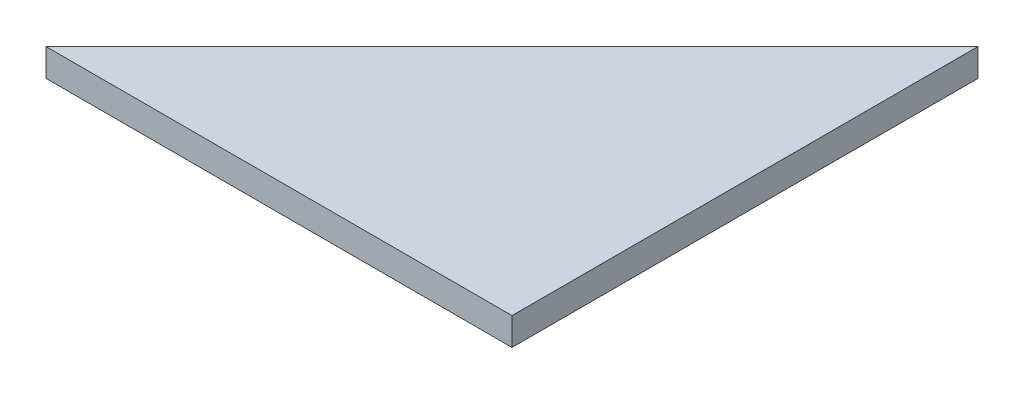
SolidWorks part; units mm, degrees
ref_plane "Front Plane" through (0, 0, 0) normal (0, 0, 1) x (1, 0, 0)
ref_plane "Top Plane" through (0, 0, 0) normal (0, 1, 0) x (1, 0, 0)
ref_plane "Right Plane" through (0, 0, 0) normal (1, 0, 0) x (0, 0, -1)
sketch "Sketch1" plane through (0, 0, 0) normal (0, 1, 0) x (1, 0, 0)
  line L0 (0, 0) -> (53.64, 53.64)
  line L1 (53.64, 53.64) -> (53.64, 0)
  line L2 (53.64, 0) -> (0, 0)
  line L3 (0, 0) -> (-14.0017, 0) construction
  dimension "D1" = 45
  dimension "D2" = 53.64
extrude "Boss-Extrude1" add sketch "Sketch1" along normal blind 3.175
sketch "Sketch2" plane through (0, 3.175, 0) normal (0, 1, 0) x (1, 0, 0)
  line L0 (33.64, -17.1503) -> (33.64, 13.412) construction
  line L1 (30.14, 3.175) -> (32.17, 3.175)
  line L2 (30.14, 3.175) -> (30.14, 0)
  line L3 (30.14, 0) -> (37.14, 0)
  line L4 (37.14, 3.175) -> (37.14, 0)
  line L5 (0, 0) -> (53.64, 0) construction
  line L6 (53.64, 0) -> (53.64, 53.64) construction
  line L7 (33.64, 9.925) -> (33.64, 3.175) construction
  line L8 (35.11, 7.85) -> (36.89, 7.85)
  line L9 (32.17, 9.925) -> (35.11, 9.925)
  line L10 (32.17, 9.925) -> (32.17, 7.85)
  line L12 (35.11, 9.925) -> (35.11, 7.85)
  line L13 (30.39, 7.85) -> (32.17, 7.85)
  line L14 (30.39, 7.85) -> (30.39, 5.25)
  line L15 (30.39, 5.25) -> (32.17, 5.25)
  line L16 (36.89, 7.85) -> (36.89, 5.25)
  line L17 (32.17, 5.25) -> (32.17, 3.175)
  line L18 (35.11, 5.25) -> (36.89, 5.25)
  line L19 (35.11, 5.25) -> (35.11, 3.175)
  line L20 (31.9575, 5.25) -> (35.7815, 5.25) construction
  line L21 (35.11, 3.175) -> (37.14, 3.175)
  line L22 (26.82, 26.82) -> (36.3598, 17.2802) construction
  line L23 (53.64, 53.64) -> (0, 0) construction
  line L24 (24.3451, 24.3451) -> (26.5902, 22.1001)
  line L25 (26.5902, 22.1001) -> (28.0256, 23.5355)
  line L26 (31.5399, 27.0498) -> (29.2949, 29.2949)
  line L27 (29.2949, 29.2949) -> (24.3451, 24.3451)
  line L28 (28.0256, 23.5355) -> (29.4964, 22.0647)
  line L29 (29.4964, 22.0647) -> (28.2377, 20.8061)
  line L30 (28.2377, 20.8061) -> (30.0762, 18.9676)
  line L31 (30.0762, 18.9676) -> (31.3349, 20.2262)
  line L32 (31.3349, 20.2262) -> (32.7986, 18.7625)
  line L33 (32.7986, 18.7625) -> (33.838, 19.802)
  line L34 (30.1045, 25.6144) -> (31.5753, 24.1436)
  line L35 (31.5753, 24.1436) -> (32.8339, 25.4023)
  line L36 (32.8339, 25.4023) -> (34.6724, 23.5638)
  line L37 (34.6724, 23.5638) -> (33.4138, 22.3051)
  line L38 (34.8775, 20.8414) -> (33.838, 19.802)
  line L39 (33.4138, 22.3051) -> (34.8775, 20.8414)
  line L40 (30.1045, 25.6144) -> (31.5399, 27.0498)
  point P8 (33.3183, 19.2822)
  dimension "D1" = 3.175
  dimension "D2" = 7
  dimension "D3" = 20
  dimension "D4" = 2.6
  dimension "D5" = 6.5
  dimension "D6" = 2.94
  dimension "D7" = 3.175
  dimension "D8" = 7
  dimension "D9" = 6.5
  dimension "D10" = 3.25
  dimension "D11" = 2.08
  dimension "D12" = 2.6
  dimension "D13" = 1.47
  dimension "D14" = 1.47
  dimension "D15" = 6.75
extrude "Cut-Extrude1" [suppressed] cut sketch "Sketch2" against normal blind 3.175
